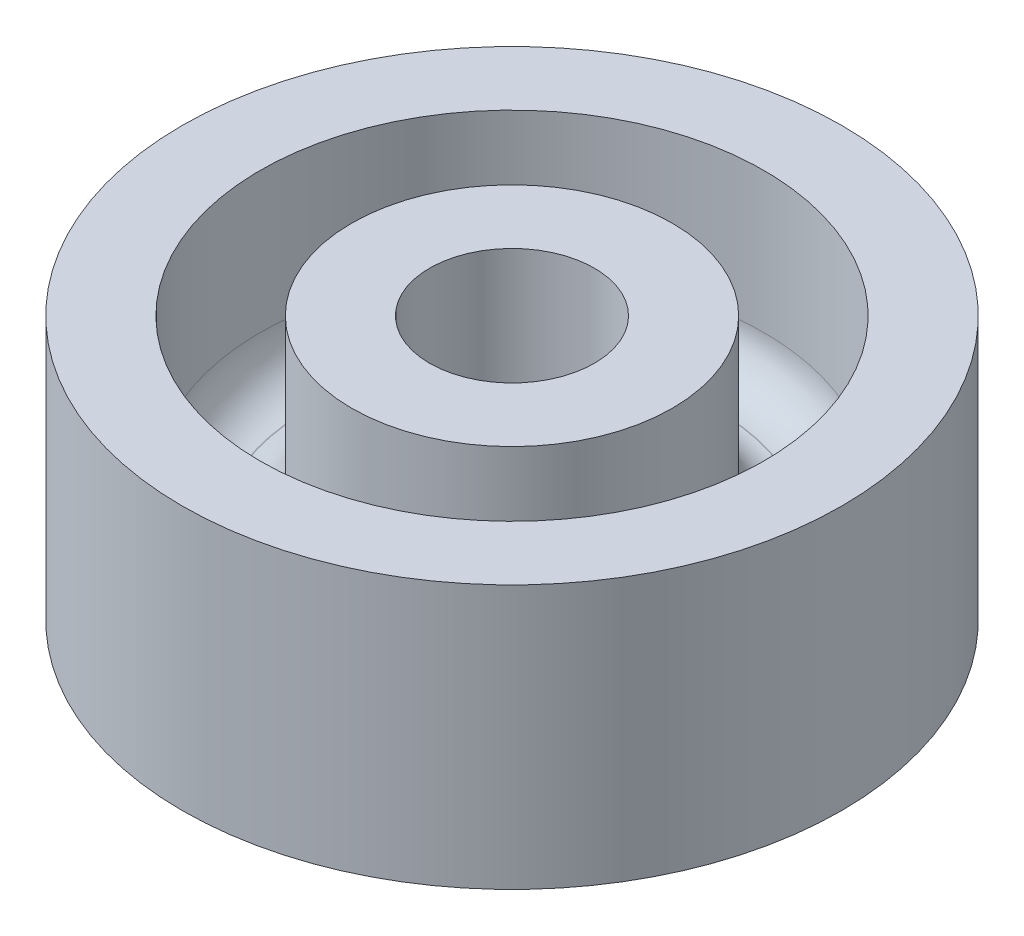
SolidWorks part; units mm, degrees
ref_plane "Front Plane" through (0, 0, 0) normal (0, 0, 1) x (1, 0, 0)
ref_plane "Top Plane" through (0, 0, 0) normal (0, 1, 0) x (1, 0, 0)
ref_plane "Right Plane" through (0, 0, 0) normal (1, 0, 0) x (0, 0, -1)
sketch "Sketch1" plane through (0, 0, 0) normal (0, 1, 0) x (1, 0, 0)
  circle A0 centre (0, 0) radius 12.7
  dimension "D1" = 25.4
extrude "Boss-Extrude1" add sketch "Sketch1" along normal blind 10.16
sketch "Sketch2" plane through (0, 10.16, 0) normal (0, 1, 0) x (1, 0, 0)
  circle A0 centre (0, 0) radius 3.175
  circle A1 centre (0, 0) radius 6.175
  circle A2 centre (0, 0) radius 9.7
  circle A3 centre (0, 0) radius 12.7 construction
  dimension "D1" = 6.35
  dimension "D2" = 3
  dimension "D3" = 3
extrude "Cut-Extrude1" cut sketch "Sketch2" against normal offset from surface (7.16 mm away) 3 contours A0 | A2 A1 up to face at (0, 0, 12.7)
fillet "Fillet1" radius 1.75 2 edges at (0, 3, 6.175) (0, 3, 9.7)
